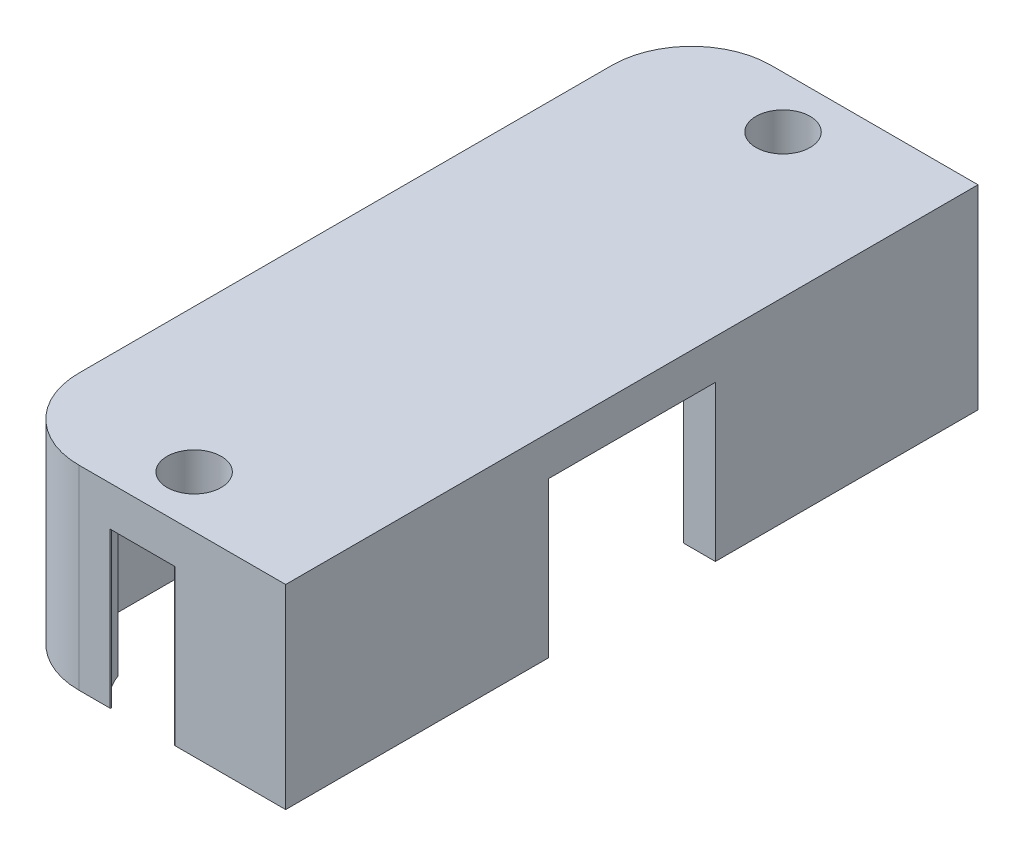
SolidWorks part; units mm, degrees
ref_plane "Front Plane" through (0, 0, 0) normal (0, 0, 1) x (1, 0, 0)
ref_plane "Top Plane" through (0, 0, 0) normal (0, 1, 0) x (1, 0, 0)
ref_plane "Right Plane" through (0, 0, 0) normal (1, 0, 0) x (0, 0, -1)
sketch "Sketch1" plane through (0, 0, 0) normal (0, 1, 0) x (1, 0, 0)
  line L1 (9, -21.75) -> (-9, -21.75)
  line L2 (9, -21.75) -> (9, 21.75)
  line L3 (9, 21.75) -> (-9, 21.75)
  line L4 (-9, -21.75) -> (-9, 21.75)
  line L5 (9, -21.75) -> (-9, 21.75) construction
  line L6 (9, 21.75) -> (-9, -21.75) construction
  point P0 (0, 0)
  dimension "D1" = 43.5
  dimension "D2" = 18
extrude "Boss-Extrude1" add sketch "Sketch1" along normal blind 2.5
fillet "Fillet1" radius 5 2 edges at (-9, 1.25, -21.75) (-9, 1.25, 21.75)
sketch "Sketch2" plane through (0, 0, 0) normal (0, -1, 0) x (1, 0, 0)
  line L0 (9, -21.75) -> (-4, -21.75) construction
  line L1 (-9, -16.75) -> (-9, 16.75) construction
  line L2 (-4, 21.75) -> (9, 21.75) construction
  line L3 (9, -21.75) -> (-4, -21.75)
  line L4 (-9, -16.75) -> (-9, 16.75)
  line L5 (-4, 21.75) -> (9, 21.75)
  line L6 (9, -19.75) -> (-4, -19.75)
  line L7 (-7, -16.75) -> (-7, 16.75)
  line L8 (-4, 19.75) -> (9, 19.75)
  line L9 (9, 21.75) -> (9, 19.75)
  line L10 (9, -19.75) -> (9, -21.75)
  arc A0 (-9, -16.75) -> (-4, -21.75) centre (-4, -16.75) ccw construction
  arc A1 (-4, 21.75) -> (-9, 16.75) centre (-4, 16.75) ccw construction
  arc A2 (-9, -16.75) -> (-4, -21.75) centre (-4, -16.75) ccw
  arc A3 (-4, 21.75) -> (-9, 16.75) centre (-4, 16.75) ccw
  arc A4 (-7, -16.75) -> (-4, -19.75) centre (-4, -16.75) ccw
  arc A5 (-4, 19.75) -> (-7, 16.75) centre (-4, 16.75) ccw
  dimension "D1" = 2
extrude "Boss-Extrude2" add sketch "Sketch2" along normal blind 9.75 contours L7 A5 L8 L9 L5 A3 L4 A2 L3 L10 L6 A4
sketch "Sketch3" plane through (0, 0, 0) normal (0, -1, 0) x (1, 0, 0)
  line L0 (9, 21.75) -> (9, 19.75) construction
  line L1 (9, 19.75) -> (7, 19.75)
  line L2 (9, 19.75) -> (9, 5.25)
  line L3 (9, 5.25) -> (7, 5.25)
  line L4 (7, 19.75) -> (7, 5.25)
  line L5 (9, -19.75) -> (7, -19.75)
  line L6 (9, -19.75) -> (9, -5.25)
  line L7 (9, -5.25) -> (7, -5.25)
  line L8 (7, -19.75) -> (7, -5.25)
  dimension "D1" = 10.5
extrude "Boss-Extrude3" add sketch "Sketch3" along normal up to surface (9.75 mm away) up to face at (-1.2761, -9.75, 0)
hole_wizard "M3 Clearance Hole1" positions "Sketch5" profile "Sketch6" hole size "M3" standard "ANSI Metric" end condition through all
sketch "Sketch5" plane through (0, 2.5, 0) normal (0, 1, 0) x (1, 0, 0)
  line L0 (0, -18.5) -> (0, 18.5)
  point P0 (0, -18.5)
  point P2 (0, 18.5)
  dimension "D1" = 37
sketch "Sketch6" plane through (0, 2.5, 18.5) normal (1, 0, 0) x (0, 0, 1)
  line L0 (0, 0) -> (0, 12.25)
  line L1 (0, 12.25) -> (1.7, 12.25)
  line L2 (1.7, 12.25) -> (1.7, 0)
  line L5 (1.7, 0) -> (0, 0)
  line L11 (0, -6.35) -> (0, 107.95) construction
  dimension "Thru Hole Dia." = 3.4
  dimension "Thru Hole Depth" = 12.25
sketch "Sketch7" plane through (0, 0, 0) normal (0, -1, 0) x (1, 0, 0)
  circle A0 centre (0, 18.5) radius 3.75
  circle A1 centre (0, -18.5) radius 3.75
  dimension "D1" = 7.5
extrude "Cut-Extrude1" cut sketch "Sketch7" along normal through all
fillet "Fillet2" radius 0.05 2 edges at (-1.8708, -4.875, 21.75) (-1.8708, -4.875, -21.75)
